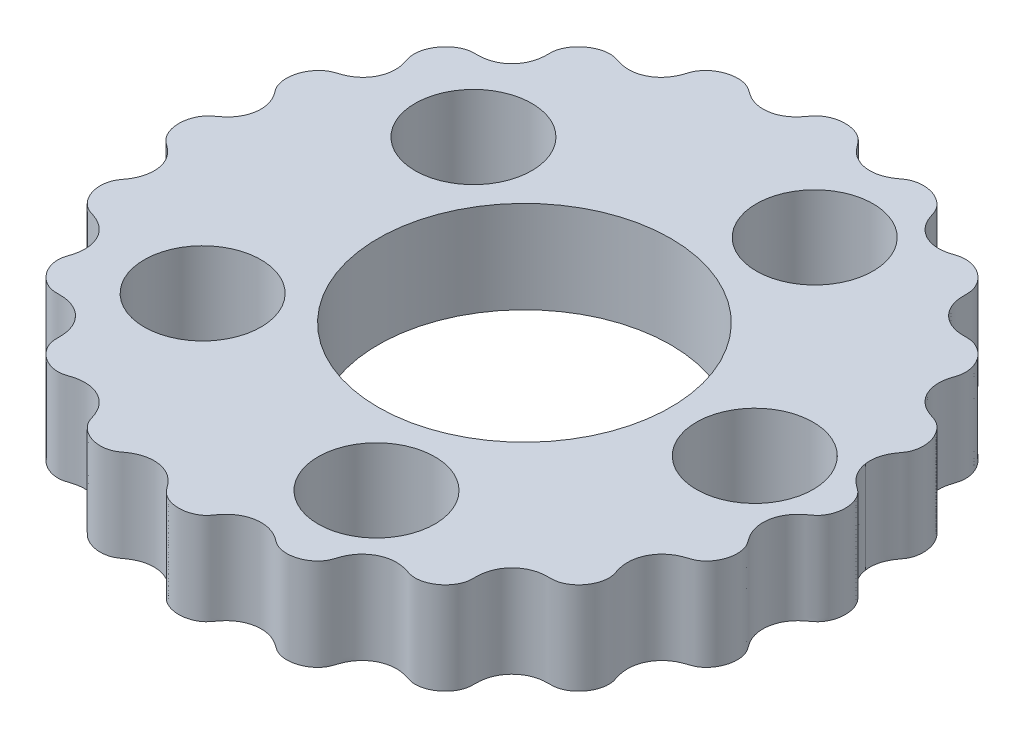
SolidWorks part; units mm, degrees
ref_plane "Front Plane" through (0, 0, 0) normal (0, 0, 1) x (1, 0, 0)
ref_plane "Top Plane" through (0, 0, 0) normal (0, 1, 0) x (1, 0, 0)
ref_plane "Right Plane" through (0, 0, 0) normal (1, 0, 0) x (0, 0, -1)
sketch "MAIN" plane through (0, 0, 0) normal (0, 1, 0) x (1, 0, 0)
  line L0 (-0.8, -20.2489) -> (-0.8, 20.2572) construction
  circle A1 centre (-0.8, 0.0042) radius 15
  circle A8 centre (14.2, 0.0042) radius 3.8
  circle A9 centre (3.8353, -14.2617) radius 3.8
  circle A10 centre (-12.9353, -8.8126) radius 3.8
  circle A11 centre (-12.9353, 8.8209) radius 3.8
  circle A12 centre (3.8353, 14.27) radius 3.8
  circle A13 centre (-0.8, 0.0042) radius 9.525
  spline S2 degree 4 poles (18.2525, 3.1443) (18.2559, 3.1229) (18.2635, 3.0801) (18.2792, 3.0022) (18.3043, 2.9005) (18.3398, 2.782) (18.3908, 2.6439) (18.4626, 2.4841) (18.5601, 2.3116) (18.6724, 2.1474) (18.7982, 1.9938) (18.9285, 1.8589) (19.0598, 1.7412) (19.1887, 1.6382) (19.3127, 1.5472) (19.4375, 1.4573) (19.5566, 1.3596) (19.6912, 1.2218) (19.8545, 0.9992) (20.0094, 0.6738) (20.108, 0.2481) (20.1093, -0.2256) (20.0191, -0.6359) (19.8709, -0.9699) (19.6893, -1.2316) (19.4944, -1.422) (19.2321, -1.6006) (18.9473, -1.8269) (18.6669, -2.1292) (18.4273, -2.5206) (18.2717, -2.9515) (18.2076, -3.404) (18.2328, -3.8021) (18.3107, -4.133) (18.4106, -4.3975) (18.5101, -4.6005) (18.6314, -4.802) (18.773, -5.0001) (18.9249, -5.203) (19.0395, -5.4403) (19.1241, -5.7389) (19.1567, -6.0963) (19.1136, -6.5032) (18.9694, -6.9388) (18.7551, -7.2996) (18.5238, -7.5523) (18.3149, -7.7122) (18.1551, -7.8044) (18.0202, -7.8641) (17.8807, -7.9119) (17.7404, -7.9567) (17.5327, -8.0292) (17.264, -8.1462) (16.9506, -8.3377) (16.6251, -8.6346) (16.3621, -8.9913) (16.1736, -9.3954) (16.0689, -9.8314) (16.0543, -10.2258) (16.096, -10.5602) (16.1637, -10.8415) (16.2382, -11.0712) (16.317, -11.3099) (16.3486, -11.5692) (16.3341, -11.8765) (16.2528, -12.2229) (16.0828, -12.5993) (15.8016, -12.9759) (15.4661, -13.2618) (15.1393, -13.4334) (14.8636, -13.5145) (14.6589, -13.5412) (14.4941, -13.5448) (14.2882, -13.5432) (14.0239, -13.5529) (13.7036, -13.5995) (13.3383, -13.7133) (12.983, -13.897) (12.6649, -14.1419) (12.3948, -14.441) (12.1823, -14.7852) (12.0341, -15.1631) (11.9596, -15.5316) (11.9419, -15.8406) (11.9455, -16.0841) (11.9391, -16.2981) (11.9051, -16.5102) (11.8103, -16.792) (11.62, -17.1208) (11.337, -17.4361) (10.9575, -17.7071) (10.5691, -17.8722) (10.2356, -17.939) (9.9745, -17.9448) (9.7925, -17.9253) (9.6495, -17.8943) (9.5097, -17.8513) (9.3709, -17.8055) (9.1566, -17.7408) (8.8615, -17.6758) (8.4808, -17.6481) (8.0244, -17.7062) (7.5924, -17.855) (7.2026, -18.0866) (6.8696, -18.3894) (6.6374, -18.7036) (6.4834, -18.9998) (6.3916, -19.236) (6.3374, -19.4008) (6.2816, -19.5727) (6.2126, -19.7479) (6.1003, -19.9376) (5.9088, -20.1682) (5.6418, -20.3932) (5.2892, -20.5906) (4.8505, -20.7249) (4.4275, -20.7587) (4.0798, -20.7126) (3.8226, -20.6287) (3.6508, -20.5446) (3.5216, -20.4628) (3.3675, -20.3501) (3.1526, -20.1964) (2.8589, -20.0275) (2.4716, -19.8828) (2.0284, -19.8107) (1.5841, -19.8281) (1.1562, -19.9318) (0.7609, -20.1148) (0.4543, -20.3348) (0.2242, -20.5603) (0.0473, -20.7737) (-0.0876, -20.9624) (-0.2316, -21.1566) (-0.4176, -21.326) (-0.6648, -21.4878) (-0.9788, -21.6213) (-1.3598, -21.705) (-1.7988, -21.7098) (-2.1855, -21.6329) (-2.509, -21.5015) (-2.7623, -21.3413) (-2.9278, -21.1956) (-3.0476, -21.0503) (-3.1537, -20.9041) (-3.2562, -20.764) (-3.4165, -20.5678) (-3.6545, -20.3337) (-3.9725, -20.1066) (-4.3827, -19.9215) (-4.825, -19.8217) (-5.2818, -19.8137) (-5.7339, -19.8994) (-6.0873, -20.0435) (-6.3479, -20.1965) (-6.5318, -20.3242) (-6.6496, -20.4107) (-6.7693, -20.4948) (-6.8957, -20.5684) (-7.0628, -20.6433) (-7.3129, -20.7184) (-7.6507, -20.758) (-8.0711, -20.721) (-8.5158, -20.5805) (-8.8824, -20.3681) (-9.1649, -20.1141) (-9.3422, -19.8755) (-9.44, -19.6842) (-9.5003, -19.5163) (-9.5438, -19.3805) (-9.6101, -19.1835) (-9.714, -18.9303) (-9.8812, -18.6341) (-10.1388, -18.3205) (-10.4473, -18.0589) (-10.7966, -17.8578) (-11.1749, -17.7233) (-11.5695, -17.6583) (-11.9522, -17.663) (-12.2712, -17.7176) (-12.5255, -17.7901) (-12.7208, -17.8552) (-12.8787, -17.9028) (-13.0816, -17.9406) (-13.3689, -17.9486) (-13.7327, -17.8864) (-14.1401, -17.7182) (-14.5239, -17.447) (-14.8019, -17.1415) (-14.9863, -16.8371) (-15.095, -16.5494) (-15.1451, -16.293) (-15.144, -16.0417) (-15.1441, -15.8002) (-15.1666, -15.5117) (-15.2303, -15.1808) (-15.3661, -14.8102) (-15.6004, -14.4279) (-15.9045, -14.1018) (-16.2648, -13.8438) (-16.6662, -13.6621) (-17.0234, -13.5767) (-17.3151, -13.5485) (-17.535, -13.5438) (-17.6823, -13.5445) (-17.8297, -13.5422) (-17.9765, -13.5271) (-18.157, -13.4888) (-18.405, -13.4012) (-18.7032, -13.2324) (-19.0184, -12.9555) (-19.2902, -12.5857) (-19.4569, -12.2121) (-19.5364, -11.8621) (-19.5482, -11.552) (-19.5125, -11.2908) (-19.4308, -11.051) (-19.3574, -10.8188) (-19.2914, -10.5346) (-19.2533, -10.1971) (-19.2731, -9.7997) (-19.3863, -9.3583) (-19.5871, -8.9478) (-19.8681, -8.586) (-20.217, -8.2878) (-20.5771, -8.0869) (-20.9179, -7.9597) (-21.2226, -7.8709) (-21.4668, -7.7501) (-21.7203, -7.5573) (-21.9645, -7.2855) (-22.1771, -6.9231) (-22.3222, -6.4722) (-22.36, -6.0368) (-22.3132, -5.6795) (-22.2267, -5.4174) (-22.1413, -5.2447) (-22.0582, -5.115) (-21.9673, -4.9909) (-21.8775, -4.866) (-21.7867, -4.7282) (-21.6982, -4.5758) (-21.616, -4.4072) (-21.5438, -4.2222) (-21.4877, -4.0313) (-21.4483, -3.8371) (-21.4293, -3.663) (-21.4236, -3.5159) (-21.4264, -3.3922) (-21.434, -3.2874) (-21.443, -3.2092) (-21.4491, -3.1658) (-21.4525, -3.1443) knots 0.062412 0.062412 0.062412 0.062412 0.062412 0.06356 0.064708 0.065855 0.067003 0.069298 0.071593 0.073888 0.076184 0.078479 0.080774 0.082553 0.084332 0.086111 0.08789 0.089668 0.091447 0.095005 0.100606 0.106208 0.111478 0.116748 0.119878 0.123007 0.126137 0.129267 0.13454 0.139813 0.145086 0.150359 0.155581 0.160804 0.163415 0.166026 0.168637 0.171249 0.174275 0.177302 0.180329 0.183356 0.188577 0.193798 0.19911 0.204423 0.207831 0.209535 0.211238 0.212942 0.214646 0.21635 0.218053 0.223116 0.228179 0.233242 0.238305 0.243486 0.248667 0.253849 0.25644 0.25903 0.262031 0.265031 0.268031 0.271032 0.27621 0.281388 0.286995 0.292602 0.296412 0.298318 0.300223 0.302128 0.304034 0.307844 0.312446 0.317047 0.321648 0.32625 0.330919 0.335589 0.340258 0.344928 0.348227 0.349876 0.351526 0.354825 0.358123 0.363551 0.368978 0.374256 0.379533 0.382914 0.384604 0.386294 0.387984 0.389675 0.391365 0.393055 0.39834 0.403624 0.408909 0.414194 0.419326 0.424458 0.429589 0.432155 0.434721 0.43617 0.437618 0.440515 0.443412 0.44631 0.451439 0.456568 0.46197 0.467372 0.470904 0.47267 0.474436 0.476202 0.477968 0.4815 0.486659 0.491818 0.496977 0.502136 0.507093 0.51205 0.517007 0.519485 0.521964 0.524855 0.527745 0.530636 0.533527 0.538479 0.543432 0.548561 0.55369 0.556588 0.559485 0.562382 0.56383 0.565279 0.567845 0.570411 0.575542 0.580674 0.585806 0.591091 0.596376 0.60166 0.606945 0.608635 0.610325 0.612016 0.613706 0.615396 0.617086 0.620467 0.625744 0.631022 0.636449 0.641877 0.645175 0.648474 0.650124 0.651773 0.653423 0.655072 0.659742 0.664411 0.669081 0.67375 0.678352 0.682953 0.687554 0.692156 0.695966 0.697872 0.699777 0.701682 0.703588 0.707398 0.713005 0.718612 0.72379 0.728968 0.731969 0.734969 0.737969 0.74097 0.74356 0.746151 0.751333 0.756514 0.761695 0.766758 0.771821 0.776884 0.781947 0.78365 0.785354 0.787058 0.788762 0.790465 0.792169 0.795577 0.80089 0.806202 0.811423 0.816644 0.819671 0.822698 0.825725 0.828751 0.831363 0.833974 0.839196 0.844419 0.849641 0.854914 0.860187 0.86546 0.870733 0.873863 0.876993 0.880122 0.883252 0.888522 0.893792 0.899394 0.904995 0.908553 0.910332 0.91211 0.913889 0.915668 0.917447 0.919226 0.921521 0.923816 0.926112 0.928407 0.930702 0.932997 0.934145 0.935292 0.93644 0.937588 0.937588 0.937588 0.937588 0.937588
  spline S3 degree 4 poles (18.2525, 3.1443) (18.25, 3.1602) (18.2454, 3.1921) (18.2364, 3.2655) (18.2265, 3.385) (18.2249, 3.5103) (18.2325, 3.6578) (18.2503, 3.804) (18.2781, 3.9485) (18.3157, 4.0909) (18.3809, 4.2839) (18.469, 4.4789) (18.5812, 4.6725) (18.7143, 4.864) (18.8257, 5.0135) (18.928, 5.1698) (19.0093, 5.3383) (19.1006, 5.6028) (19.1575, 5.9733) (19.1281, 6.4396) (18.9771, 6.9045) (18.7698, 7.2645) (18.5611, 7.5126) (18.3864, 7.6726) (18.2079, 7.7978) (18.0314, 7.891) (17.8441, 7.9589) (17.6542, 8.0179) (17.4204, 8.103) (17.1126, 8.249) (16.7568, 8.4984) (16.399, 8.9044) (16.1413, 9.4426) (16.0532, 9.9779) (16.0885, 10.4174) (16.1652, 10.7363) (16.2306, 10.9438) (16.2856, 11.1089) (16.3392, 11.3201) (16.3673, 11.6365) (16.3131, 12.0517) (16.1216, 12.5375) (15.8205, 12.9462) (15.492, 13.233) (15.1971, 13.4049) (14.9712, 13.4973) (14.7581, 13.5524) (14.5632, 13.5762) (14.3674, 13.5767) (14.1717, 13.5763) (13.9761, 13.587) (13.7818, 13.612) (13.5021, 13.6718) (13.1474, 13.8016) (12.7422, 14.0528) (12.3518, 14.4732) (12.1088, 14.9426) (12.0051, 15.3634) (11.9776, 15.6957) (11.9761, 15.931) (11.9775, 16.1192) (11.9567, 16.3542) (11.8735, 16.6666) (11.6862, 17.0328) (11.3553, 17.4187) (10.9589, 17.6989) (10.5711, 17.8648) (10.2427, 17.9376) (10.0013, 17.9572) (9.7817, 17.9456) (9.5872, 17.9093) (9.3991, 17.8494) (9.2118, 17.7877) (9.0211, 17.7367) (8.8272, 17.6997) (8.5369, 17.669) (8.1493, 17.6838) (7.6672, 17.806) (7.1451, 18.1109) (6.7707, 18.5078) (6.5541, 18.8909) (6.438, 19.1944) (6.3732, 19.3967) (6.3193, 19.5579) (6.2324, 19.7523) (6.0646, 20.0119) (5.7783, 20.3007) (5.378, 20.5479) (4.9137, 20.7034) (4.4605, 20.7547) (4.0911, 20.7217) (3.8114, 20.6415) (3.6204, 20.5527) (3.4927, 20.4781) (3.3789, 20.3998) (3.2548, 20.3079) (3.1142, 20.2105) (2.932, 20.0988) (2.7019, 19.9845) (2.3988, 19.8789) (2.019, 19.8157) (1.5725, 19.8257) (1.0792, 19.9512) (0.6504, 20.1858) (0.3366, 20.4675) (0.1352, 20.7101) (-0.0139, 20.9145) (-0.1626, 21.1202) (-0.4266, 21.3623) (-0.8327, 21.5805) (-1.3423, 21.7091) (-1.8566, 21.7012) (-2.286, 21.5977) (-2.6006, 21.4533) (-2.8094, 21.3184) (-2.9604, 21.1875) (-3.0624, 21.0763) (-3.1399, 20.9775) (-3.1994, 20.8965) (-3.2585, 20.8153) (-3.3188, 20.735) (-3.397, 20.6367) (-3.496, 20.523) (-3.6202, 20.3983) (-3.8446, 20.2088) (-4.1742, 20.0044) (-4.6431, 19.8359) (-5.2485, 19.7967) (-5.7777, 19.9166) (-6.1668, 20.11) (-6.4266, 20.2873) (-6.5851, 20.4042) (-6.7151, 20.4936) (-6.8879, 20.5891) (-7.1602, 20.693) (-7.5418, 20.7577) (-8.0338, 20.7282) (-8.5661, 20.5591) (-8.9985, 20.2872) (-9.3173, 19.9542) (-9.4935, 19.6424) (-9.5714, 19.4007) (-9.65, 19.1603) (-9.7667, 18.8673) (-9.978, 18.5025) (-10.3133, 18.1468) (-10.7437, 17.875) (-11.1653, 17.7275) (-11.546, 17.6703) (-11.8669, 17.6771) (-12.121, 17.7146) (-12.3289, 17.7646) (-12.4926, 17.8137) (-12.6391, 17.8628) (-12.7715, 17.9021) (-12.9161, 17.9335) (-13.1252, 17.959) (-13.416, 17.9488) (-13.7775, 17.8661) (-14.1926, 17.6773) (-14.5861, 17.3859) (-14.8905, 17.0271) (-15.0735, 16.6639) (-15.1528, 16.3652) (-15.1754, 16.1535) (-15.1769, 15.9835) (-15.176, 15.7711) (-15.1927, 15.4466) (-15.2802, 15.0153) (-15.5136, 14.5221) (-15.916, 14.0708) (-16.3789, 13.779) (-16.7951, 13.6402) (-17.133, 13.589) (-17.3793, 13.5761) (-17.5765, 13.5769) (-17.7739, 13.5757) (-17.9701, 13.5501) (-18.1826, 13.4934) (-18.4061, 13.4001) (-18.6959, 13.2294) (-19.0135, 12.9517) (-19.3039, 12.5628) (-19.4993, 12.0935) (-19.5643, 11.6874) (-19.5469, 11.3645) (-19.4941, 11.1347) (-19.4346, 10.956) (-19.3633, 10.7317) (-19.2868, 10.4073) (-19.2553, 9.975) (-19.3414, 9.4535) (-19.5828, 8.933) (-19.8906, 8.5689) (-20.1878, 8.3358) (-20.4353, 8.1925) (-20.6124, 8.1087) (-20.7951, 8.0381) (-20.9813, 7.9781) (-21.1674, 7.917) (-21.3454, 7.8342) (-21.531, 7.7159) (-21.7174, 7.5582) (-21.9446, 7.3036) (-22.1685, 6.9294) (-22.3285, 6.4476) (-22.3606, 5.9264) (-22.2838, 5.5148) (-22.1593, 5.2225) (-22.043, 5.0382) (-21.9397, 4.8982) (-21.8134, 4.7211) (-21.6419, 4.4415) (-21.4726, 4.0344) (-21.3909, 3.4981) (-21.4697, 2.9066) (-21.6845, 2.4099) (-21.9458, 2.0627) (-22.1934, 1.8287) (-22.3895, 1.6756) (-22.5519, 1.5608) (-22.7091, 1.4384) (-22.8481, 1.2951) (-22.9791, 1.1209) (-23.0959, 0.9148) (-23.2177, 0.6143) (-23.3036, 0.2078) (-23.3036, -0.2809) (-23.1874, -0.7335) (-23.0188, -1.0682) (-22.8503, -1.2916) (-22.7209, -1.4267) (-22.5753, -1.5438) (-22.4231, -1.6515) (-22.2373, -1.7926) (-22.0708, -1.942) (-21.9267, -2.1002) (-21.8051, -2.2636) (-21.7254, -2.3874) (-21.6542, -2.5162) (-21.5921, -2.6498) (-21.5393, -2.7877) (-21.5022, -2.9073) (-21.4745, -3.0245) (-21.4605, -3.0965) (-21.455, -3.1285) (-21.4525, -3.1443) knots 0.063609 0.063609 0.063609 0.063609 0.063609 0.064458 0.065307 0.067005 0.068703 0.070402 0.0721 0.073798 0.075496 0.077194 0.0815 0.083653 0.085806 0.087958 0.090111 0.092264 0.094417 0.100851 0.107286 0.113599 0.116755 0.119912 0.122208 0.124504 0.1268 0.129096 0.131392 0.133688 0.13828 0.144787 0.151294 0.158382 0.16547 0.169487 0.171496 0.173504 0.175513 0.177521 0.181538 0.188089 0.19464 0.201359 0.204718 0.208078 0.210337 0.212596 0.214854 0.217113 0.219372 0.221631 0.22389 0.226149 0.232563 0.238978 0.24565 0.252321 0.256667 0.25884 0.261013 0.263186 0.265358 0.269704 0.275849 0.281993 0.288591 0.29189 0.295189 0.297466 0.299742 0.302018 0.304295 0.306571 0.308848 0.311124 0.3134 0.320031 0.326662 0.333804 0.340946 0.344869 0.34683 0.348792 0.350753 0.352715 0.356638 0.362993 0.369347 0.374207 0.379066 0.383919 0.386345 0.387558 0.388771 0.390744 0.392717 0.39469 0.396663 0.400609 0.404555 0.40945 0.414345 0.42109 0.427836 0.431732 0.433681 0.435629 0.439525 0.443422 0.450062 0.456701 0.463502 0.466903 0.470303 0.472622 0.474941 0.476101 0.47726 0.47842 0.479579 0.480739 0.481898 0.484217 0.486536 0.488855 0.49544 0.502026 0.50926 0.516494 0.520133 0.521952 0.523772 0.525591 0.527411 0.53105 0.537174 0.543299 0.549938 0.556578 0.560475 0.564371 0.566319 0.568268 0.572164 0.57891 0.585655 0.59055 0.595445 0.599391 0.603337 0.60531 0.607283 0.609256 0.611229 0.612442 0.613655 0.616081 0.620934 0.625793 0.630653 0.637007 0.643362 0.647285 0.649247 0.651208 0.65317 0.655131 0.659054 0.666196 0.673338 0.679969 0.6866 0.691152 0.693429 0.695705 0.697982 0.700258 0.702534 0.704811 0.70811 0.711409 0.718007 0.724151 0.730296 0.734642 0.736814 0.738987 0.74116 0.743333 0.747679 0.75435 0.761022 0.767437 0.773851 0.77611 0.778369 0.780628 0.782887 0.785146 0.787404 0.789663 0.791922 0.795282 0.798641 0.80536 0.811911 0.818462 0.822479 0.824487 0.826496 0.828504 0.830513 0.83453 0.841618 0.848706 0.855213 0.86172 0.866312 0.868608 0.870904 0.8732 0.875496 0.877792 0.880088 0.883245 0.886401 0.892714 0.899149 0.905583 0.907736 0.909889 0.912042 0.914194 0.916347 0.9185 0.922806 0.924504 0.926202 0.9279 0.929598 0.931297 0.932995 0.934693 0.935542 0.936391 0.936391 0.936391 0.936391 0.936391
  point P0 (-0.8, 0.0042)
  dimension "D1" = 30
  dimension "D2" = 7.6
  dimension "D4" = 19.05
  dimension "D3" = 5
extrude "Boss-Extrude1" add sketch "MAIN" against normal blind 6 from offset 1 contours S2 S3 A12 A1 A8 A9 A10 A11 | A12 A1 A11 A10 A9 A8 A13
